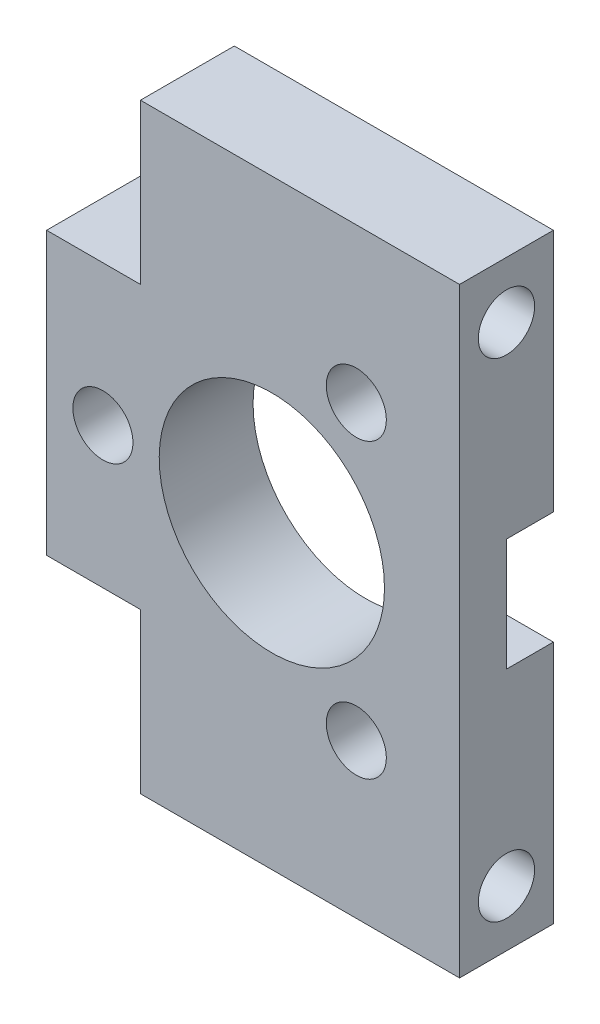
SolidWorks part; units mm, degrees
material "Alliage 1060"
ref_plane "Plan de face" through (0, 0, 0) normal (0, 0, 1) x (1, 0, 0)
ref_plane "Plan de dessus" through (0, 0, 0) normal (0, 1, 0) x (1, 0, 0)
ref_plane "Plan de droite" through (0, 0, 0) normal (1, 0, 0) x (0, 0, -1)
sketch "Esquisse1" plane through (0, 0, 0) normal (0, 0, 1) x (1, 0, 0)
  line L0 (-56.9079, 0) -> (95.1279, 0) construction
  line L1 (-7, 16) -> (10, 16)
  line L2 (-12, 7.5) -> (-12, -7.5)
  line L3 (-7, -16) -> (10, -16)
  line L4 (10, 16) -> (10, -16)
  line L5 (17.6, 150.92) -> (17.6, -150.92) construction
  line L6 (-7, 16) -> (-7, 7.5)
  line L7 (-7, 7.5) -> (-12, 7.5)
  line L8 (-12, -7.5) -> (-7, -7.5)
  line L9 (-7, -7.5) -> (-7, -16)
  circle A0 centre (0, 0) radius 6
  circle A2 centre (0, 0) radius 6 construction
  circle A3 centre (-9, 0) radius 1.6
  circle A4 centre (4.5, 7.7942) radius 1.6
  circle A5 centre (4.5, -7.7942) radius 1.6
  circle A6 centre (4.5, 7.7942) radius 0.8 construction
  circle A7 centre (-9, 0) radius 0.8 construction
  circle A8 centre (4.5, -7.7942) radius 0.8 construction
  dimension "D1" = 12
  dimension "D4" = 3.2
  dimension "D6" = 15
  dimension "D2" = 32
  dimension "D3" = 10
  dimension "D5" = 7.6
  dimension "D7" = 5
extrude "Extrusion1" add sketch "Esquisse1" along normal blind 5
sketch "Esquisse2" plane through (0, 0, 0) normal (0, 0, -1) x (-1, 0, 0)
  line L0 (-10, -16) -> (-10, 16) construction
  line L1 (-10, 3) -> (0, 3)
  line L2 (-10, 3) -> (-10, -3)
  line L3 (-10, -3) -> (0, -3)
  line L4 (0, 3) -> (0, -3)
  line L5 (0, 0) -> (-28.6671, 0) construction
  dimension "D1" = 6
extrude "Enlèv. mat.-Extru.1" cut sketch "Esquisse2" against normal blind 2.5
sketch "Esquisse3" plane through (-12, 0, 0) normal (-1, 0, 0) x (0, 0, 1)
  line L0 (2.5, -13) -> (2.5, 13) construction
  line L2 (0, 7.5) -> (0, -7.5) construction
  line L3 (5, 7.5) -> (5, -7.5) construction
  circle A0 centre (2.5, 13) radius 1.5
  circle A1 centre (2.5, -13) radius 1.5
  point P9 (2.5, 0)
  dimension "D1" = 3
  dimension "D2" = 26
extrude "Enlèv. mat.-Extru.2" cut sketch "Esquisse3" against normal through all
